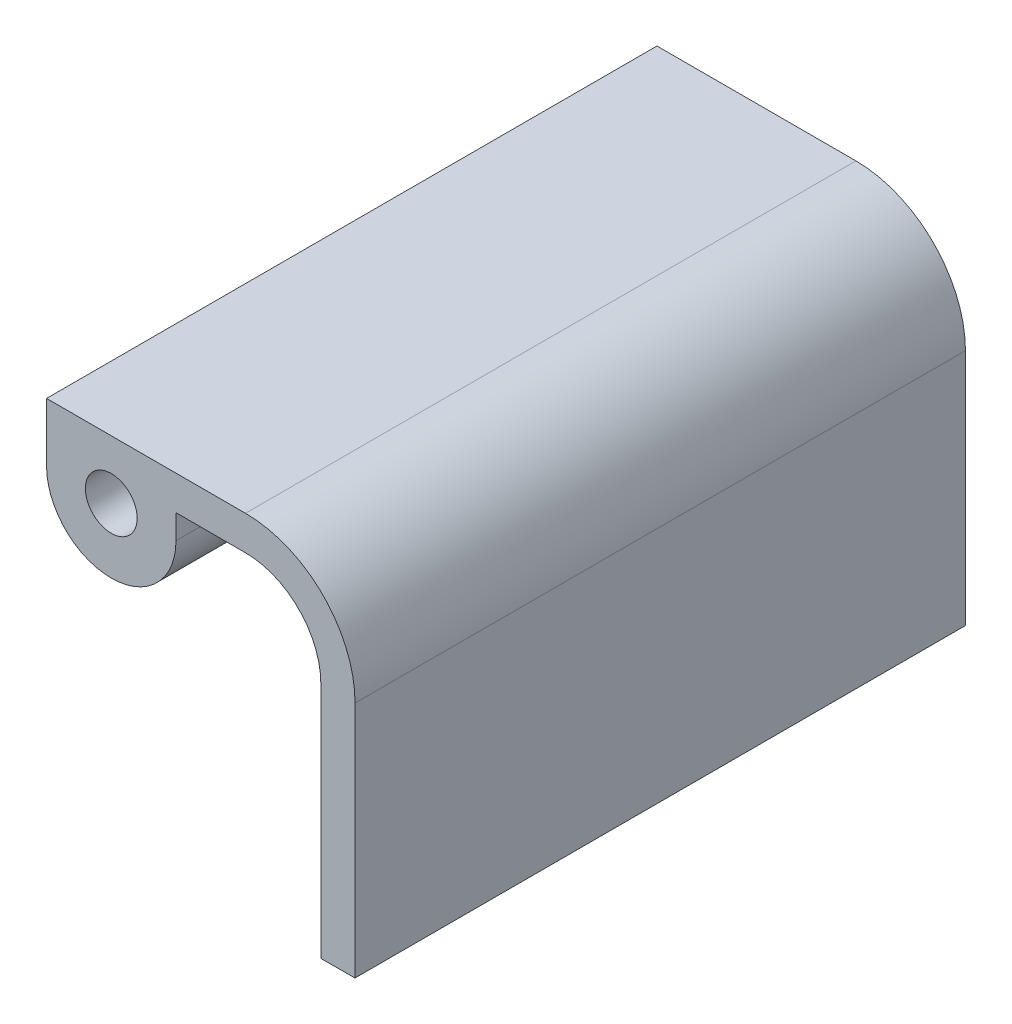
SolidWorks part; units mm, degrees
material "ABS"
ref_plane "X-Y Datum" through (0, 0, 0) normal (0, 0, 1) x (1, 0, 0)
ref_plane "X-Z Datum" through (0, 0, 0) normal (0, 1, 0) x (1, 0, 0)
ref_plane "Y-Z Datum" through (0, 0, 0) normal (1, 0, 0) x (0, 0, -1)
sketch "Sketch1" plane through (0, 0, 0) normal (0, 0, 1) x (1, 0, 0)
  line L0 (-76.1732, 182.1172) -> (-79.3482, 182.097)
  line L3 (-79.3482, 182.097) -> (-79.3482, 204.1965)
  line L4 (-76.1732, 182.1172) -> (-76.1732, 204.1965)
  line L11 (-86.3332, 211.1815) -> (-92.7782, 211.1815)
  line L12 (-86.3332, 214.3565) -> (-92.7782, 214.3565)
  line L14 (-104.7782, 214.3565) -> (-104.7782, 208.9265)
  line L15 (-92.7782, 211.1815) -> (-92.7782, 208.9265)
  line L16 (-104.7782, 214.3565) -> (-92.7782, 214.3565)
  arc A1 (-79.3482, 204.1965) -> (-86.3332, 211.1815) centre (-86.3332, 204.1965) ccw
  arc A3 (-76.1732, 204.1965) -> (-86.3332, 214.3565) centre (-86.3332, 204.1965) ccw
  arc A4 (-92.7782, 208.9265) -> (-104.7782, 208.9265) centre (-98.7782, 208.9265) cw
  circle A8 centre (-98.7782, 208.9265) radius 2.4
  dimension "D2" = 3.175
extrude "Boss-Extrude1" add sketch "Sketch1" along normal blind 56.5988
